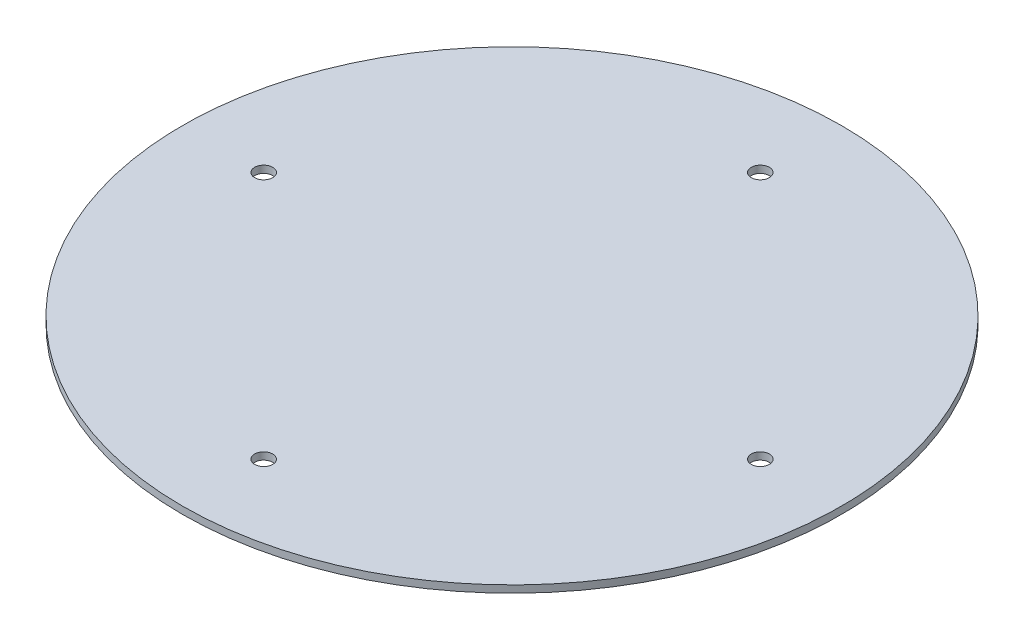
SolidWorks part; units mm, degrees
material "PET"
ref_plane "Front Plane" through (0, 0, 0) normal (0, 0, 1) x (1, 0, 0)
ref_plane "Top Plane" through (0, 0, 0) normal (0, 1, 0) x (1, 0, 0)
ref_plane "Right Plane" through (0, 0, 0) normal (1, 0, 0) x (0, 0, -1)
sketch "Sketch1" plane through (0, 0, 0) normal (0, 1, 0) x (1, 0, 0)
  arc A0 (-65, -33.2265) -> (-33.2265, -65) centre (0, 0) ccw
  arc A1 (-65, 33.2265) -> (-65, -33.2265) centre (0, 0) ccw construction
  arc A2 (33.2265, 65) -> (-33.2265, 65) centre (0, 0) ccw construction
  arc A3 (-33.2265, 65) -> (-65, 33.2265) centre (0, 0) ccw
  arc A4 (65, -33.2265) -> (65, 33.2265) centre (0, 0) ccw construction
  arc A5 (65, 33.2265) -> (33.2265, 65) centre (0, 0) ccw
  arc A6 (-33.2265, -65) -> (33.2265, -65) centre (0, 0) ccw construction
  arc A7 (33.2265, -65) -> (65, -33.2265) centre (0, 0) ccw
  circle A8 centre (0, 0) radius 73
  point P14 (0, 0)
  dimension "D1" = 146
extrude "Boss-Extrude1" add sketch "Sketch1" along normal blind 1.6 contours A7 A8 A5 A3 A0
sketch "Sketch2" plane through (0, 1.6, 0) normal (0, 1, 0) x (1, 0, 0)
  line L0 (0, 0) -> (0, 55) construction
  line L3 (0, 0) -> (55, 0) construction
  line L4 (0, 0) -> (0, -55) construction
  line L6 (-55, 0) -> (0, 0) construction
  point P0 (0, 55)
  point P2 (55, 0)
  point P4 (-55, 0)
  point P6 (0, -55)
  dimension "D1" = 55
hole_wizard "Ø4.0mm Dowel Hole1" positions "Sketch2" profile "Sketch3" hole size "Ø4.0" standard "ISO" end condition through all
sketch "Sketch3" plane through (0, 1.6, -55) normal (1, 0, 0) x (0, 0, 1)
  line L0 (0, 0) -> (0, 1.6)
  line L1 (0, 1.6) -> (2, 1.6)
  line L2 (2, 1.6) -> (2, 0)
  line L5 (2, 0) -> (0, 0)
  line L11 (0, -6.35) -> (0, 107.95) construction
  dimension "Thru Hole Dia." = 4
  dimension "Thru Hole Depth" = 1.6
